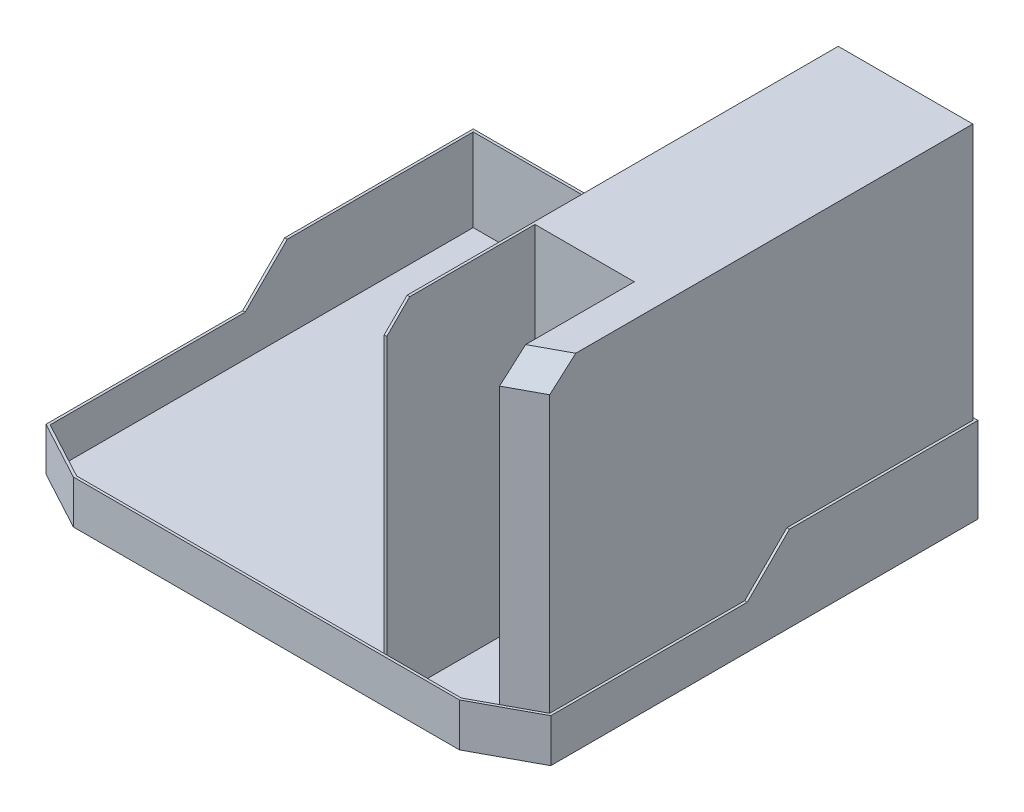
SolidWorks part; units mm, degrees
ref_plane "Front Plane" through (0, 0, 0) normal (0, 0, 1) x (1, 0, 0)
ref_plane "Top Plane" through (0, 0, 0) normal (0, 1, 0) x (1, 0, 0)
ref_plane "Right Plane" through (0, 0, 0) normal (1, 0, 0) x (0, 0, -1)
sketch "Sketch1" plane through (0, 0, 0) normal (0, 1, 0) x (1, 0, 0)
  line L0 (225.65, -262.25) -> (394.0562, -262.25)
  line L1 (-225.65, 262.25) -> (225.65, 262.25)
  line L2 (-225.65, 262.25) -> (-225.65, -262.25)
  line L3 (-225.65, -262.25) -> (225.65, -262.25)
  line L4 (225.65, 262.25) -> (225.65, -262.25) construction
  line L5 (-225.65, 262.25) -> (225.65, -262.25) construction
  line L6 (-225.65, -262.25) -> (225.65, 262.25) construction
  line L7 (394.0562, -262.25) -> (394.0562, 262.25)
  line L8 (394.0562, 262.25) -> (225.65, 262.25)
  point P0 (0, 0)
  dimension "D1" = 451.3
  dimension "D2" = 524.5
extrude "Boss-Extrude3" add sketch "Sketch1" along normal blind 370 contours L3 L0 L7 L8 L1 L2
sketch "Sketch3" plane through (0, 370, 0) normal (0, 1, 0) x (1, 0, 0)
  line L4 (-225.65, 262.25) -> (-225.65, -262.25)
  line L5 (-225.65, -262.25) -> (394.0562, -262.25)
  line L6 (394.0562, -262.25) -> (394.0562, 262.25)
  line L7 (394.0562, 262.25) -> (-225.65, 262.25)
  line L8 (-225.65, 262.25) -> (-225.65, -262.25)
  line L9 (-225.65, -262.25) -> (394.0562, -262.25)
  line L10 (394.0562, -262.25) -> (394.0562, 262.25)
  line L11 (394.0562, 262.25) -> (-225.65, 262.25)
  dimension "D1" = 0
extrude "Boss-Extrude4" add sketch "Sketch3" along normal blind 50
sketch "Sketch9" plane through (0, 0, 0) normal (0, 1, 0) x (1, 0, 0)
  line L0 (-225.65, -262.25) -> (-152.7479, -301.5406)
  line L1 (-152.7479, -301.5406) -> (321.1542, -301.5406)
  line L2 (321.1542, -301.5406) -> (394.0562, -262.25)
  line L3 (84.2031, -262.25) -> (84.2031, -301.5406) construction
  line L4 (-225.65, -262.25) -> (394.0562, -262.25) construction
  line L5 (-225.65, -262.25) -> (394.0562, -262.25)
extrude "Boss-Extrude6" add sketch "Sketch9" along normal up to surface (420 mm away) contours L1 L2 L5 L0 up to face at (84.2031, 420, 0)
chamfer "Chamfer1" distance 30 angle 45 3 edges at (357.6052, 420, 281.8953) (-189.199, 420, 281.8953) (84.2031, 420, 301.5406)
shell "Shell1" thickness 3.18
sketch "Sketch7" plane through (-225.65, 0, 0) normal (-1, 0, 0) x (0, 0, 1)
  line L0 (-19.07, 315) -> (-19.07, 230)
  line L1 (-19.07, 230) -> (20.93, 190)
  line L2 (20.93, 190) -> (80.93, 190)
  line L3 (80.93, 190) -> (120.93, 230)
  line L4 (120.93, 230) -> (120.93, 315)
  line L5 (120.93, 315) -> (-19.07, 315)
extrude "Cut-Extrude1" cut sketch "Sketch7" against normal blind 10
sketch "Sketch11" plane through (-225.65, 0, 0) normal (-1, 0, 0) x (0, 0, 1)
  line L0 (-30.8178, 101.7478) -> (20.93, 50)
  line L1 (20.93, 50) -> (377.9827, 50)
  line L2 (-30.8178, 101.7478) -> (-303.7072, 101.7478)
  line L3 (-19.07, 230) -> (20.93, 190) construction
  line L4 (-262.25, 0) -> (262.25, 0) construction
  line L5 (20.93, 190) -> (20.93, 50) construction
  line L6 (-30.8178, 101.7478) -> (-19.07, 230) construction
  dimension "D1" = 50
sketch "Sketch12" plane through (0, 0, 0) normal (0, 1, 0) x (1, 0, 0)
  line L0 (225.65, -262.25) -> (225.65, -298.3606)
  line L1 (390.8762, 259.07) -> (225.65, 259.07)
  line L2 (390.8762, -260.3514) -> (390.8762, 259.07)
  line L3 (390.8762, -262.25) -> (225.65, -262.25) construction
  line L4 (225.65, 259.07) -> (225.65, -262.25)
  line L5 (-151.9456, -298.3606) -> (320.3518, -298.3606) construction
  line L6 (225.65, -298.3606) -> (320.3518, -298.3606)
  line L7 (320.3518, -298.3606) -> (390.8762, -260.3514)
  line L8 (320.3518, -298.3606) -> (390.8762, -260.3514) construction
extrude "Boss-Extrude7" add sketch "Sketch12" along normal up to next separate body
sketch "Sketch13" plane through (0, 0, 0) normal (0, -1, 0) x (1, 0, 0)
  line L0 (225.65, 262.25) -> (225.65, 298.3606) construction
  line L1 (228.83, 116.4644) -> (350.8762, 116.4644)
  line L2 (228.83, 116.4644) -> (228.83, 350.4495)
  line L3 (228.83, 350.4495) -> (350.8762, 350.4495)
  line L4 (350.8762, 116.4644) -> (350.8762, 350.4495)
  line L5 (390.8762, 260.3514) -> (390.8762, -259.07) construction
  dimension "D1" = 3.18
  dimension "D2" = 40
extrude "Cut-Extrude3" cut sketch "Sketch13" against normal through all
split "Split2" trim tools "Sketch11" bodies to split 120 resulting bodies 125
sketch "Sketch14" plane through (0, 0, 0) normal (0, -1, 0) x (1, 0, 0)
  line L0 (394.0562, 262.25) -> (394.0562, -262.25) construction
  line L1 (321.1542, 301.5406) -> (394.0562, 262.25) construction
  line L2 (-152.7479, 301.5406) -> (321.1542, 301.5406) construction
  line L3 (-225.65, -262.25) -> (394.0562, -262.25) construction
  line L4 (-225.65, -262.25) -> (-225.65, 262.25) construction
  line L5 (-225.65, 262.25) -> (-152.7479, 301.5406) construction
  line L6 (394.0562, 262.25) -> (394.0562, -262.25)
  line L7 (321.1542, 301.5406) -> (394.0562, 262.25)
  line L8 (-152.7479, 301.5406) -> (321.1542, 301.5406)
  line L9 (-225.65, -262.25) -> (394.0562, -262.25)
  line L10 (-225.65, -262.25) -> (-225.65, 262.25)
  line L11 (-225.65, 262.25) -> (-152.7479, 301.5406)
extrude "Boss-Extrude8" add sketch "Sketch14" along normal blind 3.18
